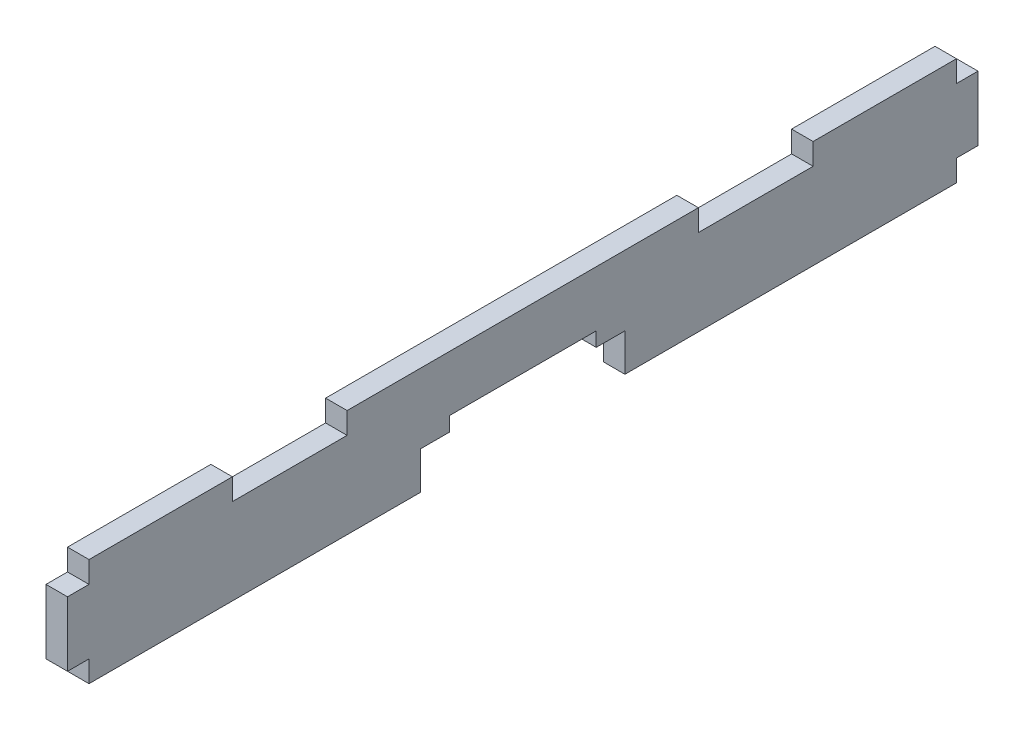
SolidWorks part; units mm, degrees
ref_plane "Front Plane" through (0, 0, 0) normal (0, 0, 1) x (1, 0, 0)
ref_plane "Top Plane" through (0, 0, 0) normal (0, 1, 0) x (1, 0, 0)
ref_plane "Right Plane" through (0, 0, 0) normal (1, 0, 0) x (0, 0, -1)
sketch "Sketch1" plane through (0, 0, 0) normal (1, 0, 0) x (0, 0, -1)
  line L1 (0, 0) -> (121, 0)
  line L2 (0, 0) -> (0, 15)
  line L3 (0, 15) -> (121, 15)
  line L4 (121, 0) -> (121, 15)
  line L5 (0, 12) -> (-3, 12)
  line L6 (0, 12) -> (0, 3)
  line L7 (0, 3) -> (-3, 3)
  line L8 (-3, 12) -> (-3, 3)
  line L9 (121, 12) -> (124, 12)
  line L10 (121, 12) -> (121, 3)
  line L11 (121, 3) -> (124, 3)
  line L12 (124, 12) -> (124, 3)
  line L13 (20, 15) -> (36, 15)
  line L14 (20, 15) -> (20, 12)
  line L15 (20, 12) -> (36, 12)
  line L16 (36, 15) -> (36, 12)
  line L17 (101, 15) -> (85, 15)
  line L18 (101, 15) -> (101, 12)
  line L19 (101, 12) -> (85, 12)
  line L20 (85, 15) -> (85, 12)
  line L21 (70.75, 0) -> (50.25, 0)
  line L22 (70.75, 0) -> (70.75, 7.25)
  line L23 (70.75, 7.25) -> (50.25, 7.25)
  line L24 (50.25, 0) -> (50.25, 7.25)
  line L25 (46.25, 0) -> (74.75, 0)
  line L26 (46.25, 0) -> (46.25, 5.25)
  line L27 (46.25, 5.25) -> (74.75, 5.25)
  line L28 (74.75, 0) -> (74.75, 5.25)
  point P13 (60.5, 15)
  point P14 (60.5, 5.25)
  point P27 (60.5, 7.25)
  dimension "D1" = 15
  dimension "D2" = 121
  dimension "D3" = 3
  dimension "D4" = 3
  dimension "D5" = 3
  dimension "D6" = 3
  dimension "D9" = 3
  dimension "D10" = 16
  dimension "D11" = 3
  dimension "D12" = 16
  dimension "D13" = 20
  dimension "D14" = 20
  dimension "D15" = 20.5
  dimension "D17" = 7.25
  dimension "D19" = 28.5
  dimension "D20" = 5.25
extrude "Boss-Extrude1" add sketch "Sketch1" along normal blind 3 contours L20 L3 L16 L15 L14 L2 L1 L4 L18 L19 | L5 L8 L7 L2 | L12 L9 L4 L11
